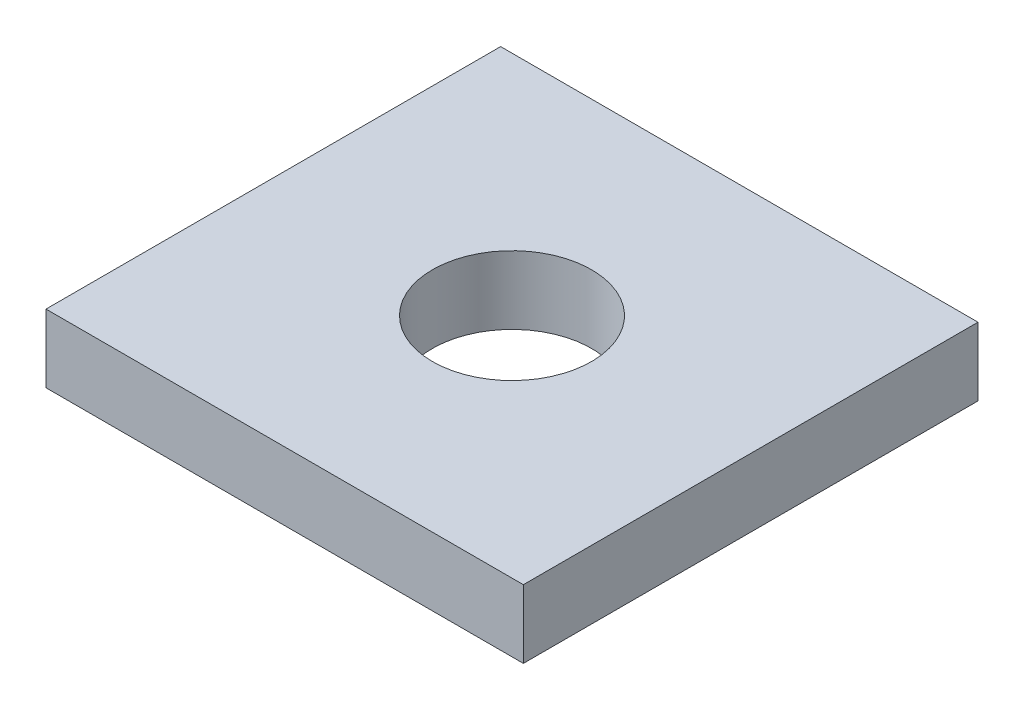
SolidWorks part; units mm, degrees
ref_plane "Front Plane" through (0, 0, 0) normal (0, 0, 1) x (1, 0, 0)
ref_plane "Top Plane" through (0, 0, 0) normal (0, 1, 0) x (1, 0, 0)
ref_plane "Right Plane" through (0, 0, 0) normal (1, 0, 0) x (0, 0, -1)
sketch "Sketch1" plane through (0, 0, 0) normal (0, 1, 0) x (1, 0, 0)
  line L1 (-21, 20) -> (21, 20)
  line L2 (-21, 20) -> (-21, -20)
  line L3 (-21, -20) -> (21, -20)
  line L4 (21, 20) -> (21, -20)
  line L5 (-21, 20) -> (21, -20) construction
  line L6 (-21, -20) -> (21, 20) construction
  point P0 (0, 0)
  dimension "D1" = 42
  dimension "D2" = 40
extrude "Boss-Extrude1" add sketch "Sketch1" along normal blind 6
sketch "Sketch2" plane through (0, 6, 0) normal (0, 1, 0) x (1, 0, 0)
  circle A0 centre (0, 0) radius 7
  dimension "D1" = 14
extrude "Cut-Extrude1" cut sketch "Sketch2" against normal blind 10
